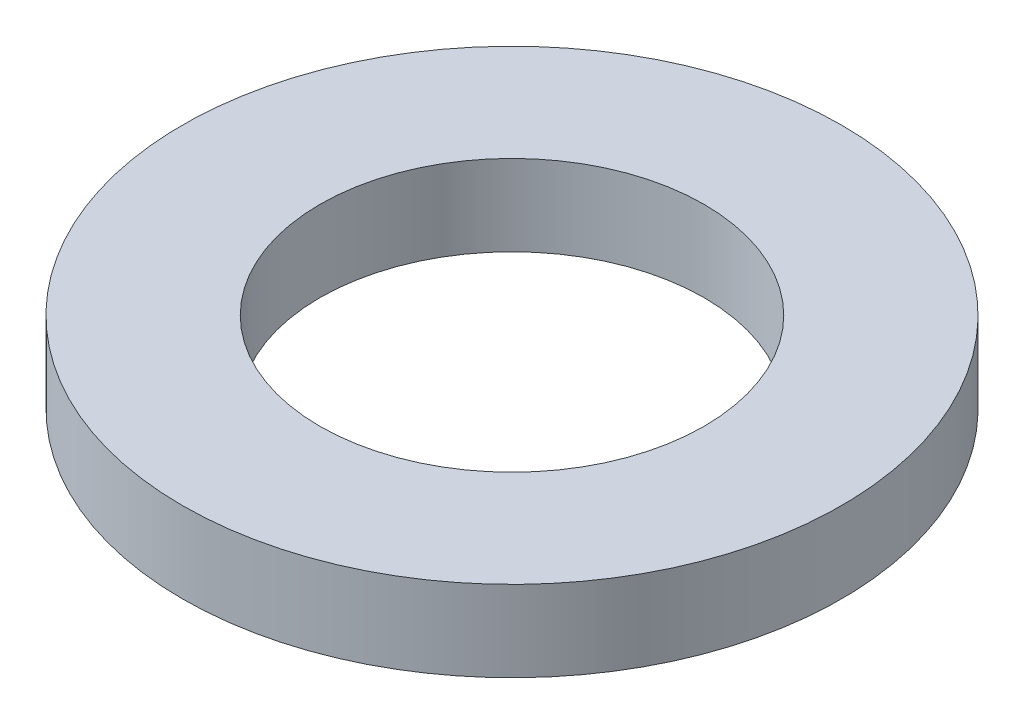
SolidWorks part; units mm, degrees
ref_plane "Front Plane" through (0, 0, 0) normal (0, 0, 1) x (1, 0, 0)
ref_plane "Top Plane" through (0, 0, 0) normal (0, 1, 0) x (1, 0, 0)
ref_plane "Right Plane" through (0, 0, 0) normal (1, 0, 0) x (0, 0, -1)
sketch "Sketch1" plane through (0, 0, 0) normal (0, 1, 0) x (1, 0, 0)
  circle A0 centre (0, 0) radius 7.1438
  dimension "OD" = 14.2875
extrude "Boss-Extrude1" add sketch "Sketch1" along normal blind 1.7526
sketch "Sketch5" plane through (0, 1.7526, 0) normal (0, 1, 0) x (-1, 0, 0)
  circle A0 centre (0, 0) radius 4.1656
  dimension "ID" = 8.3312
extrude "Cut-Extrude1" cut sketch "Sketch5" against normal through all
